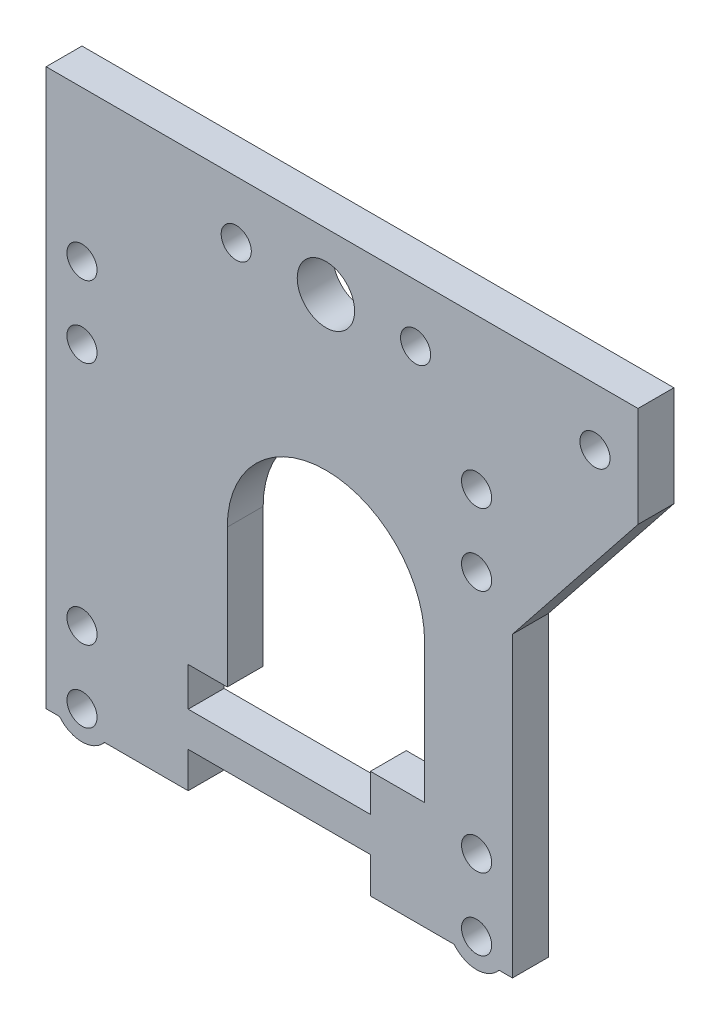
SolidWorks part; units mm, degrees
ref_plane "Front Plane" through (0, 0, 0) normal (0, 0, 1) x (1, 0, 0)
ref_plane "Top Plane" through (0, 0, 0) normal (0, 1, 0) x (1, 0, 0)
ref_plane "Right Plane" through (0, 0, 0) normal (1, 0, 0) x (0, 0, -1)
sketch "Sketch1" plane through (0, 0, 0) normal (0, 0, 1) x (1, 0, 0)
  line L1 (-65, 61.5) -> (0, 61.5)
  line L2 (-65, 61.5) -> (-65, 0)
  line L3 (-65, 0) -> (-63.1225, 0)
  line L4 (0, 61.5) -> (0, 0)
  line L5 (-56.8775, 0) -> (-45, 0)
  line L6 (-1.8775, 0) -> (0, 0)
  line L7 (-20, 0) -> (-8.1225, 0)
  line L9 (-45, 0) -> (-45, 5)
  line L10 (-45, 5) -> (-20, 5)
  line L11 (-20, 0) -> (-20, 5)
  line L13 (-45, 15.05) -> (-20, 15.05)
  line L14 (-45, 15.05) -> (-45, 9.95)
  line L15 (-45, 9.95) -> (-20, 9.95)
  line L16 (-20, 15.05) -> (-20, 9.95)
  circle A0 centre (-60, 56.5) radius 2.1
  circle A1 centre (-5, 56.5) radius 2.1
  circle A2 centre (-60, 46.5) radius 2.1
  circle A3 centre (-5, 46.5) radius 2.1
  circle A4 centre (-5, 12.5) radius 2.1
  circle A5 centre (-5, 2.5) radius 2.1
  circle A6 centre (-60, 2.5) radius 2.1
  circle A7 centre (-60, 12.5) radius 2.1
  arc A8 (-63.1225, 0) -> (-56.8775, 0) centre (-60, 2.5) ccw
  arc A9 (-8.1225, 0) -> (-1.8775, 0) centre (-5, 2.5) ccw
  point P35 (-45, 12.5)
  dimension "D1" = 4.2
  dimension "D2" = 4.2
  dimension "D3" = 4.2
  dimension "D4" = 4.2
  dimension "D5" = 5
  dimension "D6" = 5
  dimension "D7" = 10
  dimension "D8" = 10
  dimension "D9" = 5
  dimension "D11" = 55
  dimension "D14" = 8
  dimension "D15" = 8
  dimension "D10" = 5
  dimension "D12" = 61.5
  dimension "D16" = 5
  dimension "D17" = 20
  dimension "D18" = 20
  dimension "D19" = 25
  dimension "D20" = 15
  dimension "D21" = 5.1
extrude "Boss-Extrude1" add sketch "Sketch1" along normal blind 5
sketch "Sketch3" plane through (0, 0, 0) normal (0, 0, -1) x (-1, 0, 0)
  line L0 (39.75, 15.05) -> (39.75, 34.55)
  line L1 (20, 15.05) -> (45, 15.05) construction
  line L2 (12.25, 34.55) -> (12.25, 15.05)
  line L3 (39.75, 15.05) -> (12.25, 15.05)
  arc A0 (39.75, 34.55) -> (12.25, 34.55) centre (26, 34.55) ccw
  circle A1 centre (26, 34.55) radius 3.6 construction
  dimension "D1" = 27.5
extrude "Cut-Extrude2" cut sketch "Sketch3" against normal blind 5
sketch "Sketch4" plane through (0, 0, 0) normal (0, 0, -1) x (-1, 0, 0)
  line L0 (0, 41.5) -> (-17.5, 63.5)
  line L1 (-17.5, 63.5) -> (0, 41.5) construction
  line L2 (-17.5, 63.5) -> (-17.5, 77.5)
  line L5 (65, 61.5) -> (65, 77.5)
  line L10 (65, 77.5) -> (-17.5, 77.5)
  line L18 (65, 0) -> (65, 61.5)
  line L19 (65, 61.5) -> (0, 61.5)
  line L20 (0, 61.5) -> (0, 0)
  line L21 (0, 0) -> (1.8775, 0)
  line L22 (8.1225, 0) -> (20, 0)
  line L23 (20, 0) -> (20, 5)
  line L24 (20, 5) -> (45, 5)
  line L25 (45, 5) -> (45, 0)
  line L26 (45, 0) -> (56.8775, 0)
  line L27 (63.1225, 0) -> (65, 0)
  line L29 (65, 61.5) -> (0, 61.5)
  line L30 (0, 61.5) -> (0, 41.5)
  arc A0 (28.3171, 66.2394) -> (22.3115, 67.9523) centre (26, 69.5) ccw construction
  circle A1 centre (13.5, 69.5) radius 2.1 construction
  circle A2 centre (-11.5, 69.5) radius 2.1 construction
  circle A6 centre (38.5, 69.5) radius 2.1 construction
  circle A8 centre (-11.5, 69.5) radius 2.1
  arc A11 (1.8775, 0) -> (8.1225, 0) centre (5, 2.5) ccw
  arc A12 (56.8775, 0) -> (63.1225, 0) centre (60, 2.5) ccw
  circle A16 centre (13.5, 69.5) radius 2.1
  circle A17 centre (26, 69.5) radius 4
  circle A18 centre (38.5, 69.5) radius 2.1
  point P34 (13.5, 69.5)
  point P36 (-11.5, 69.5)
  point P37 (26, 69.5)
  point P39 (38.5, 69.5)
  dimension "D2" = 8
  dimension "D3" = 4.2
  dimension "D4" = 4.2
  dimension "D5" = 4.2
  dimension "D6" = 6
  dimension "D7" = 8
  dimension "D9" = 43.5
  dimension "D10" = 56
  dimension "D1" = 0
  dimension "D8" = 31
  dimension "D11" = 8
extrude "Boss-Extrude2" add sketch "Sketch4" against normal blind 5
sketch "Sketch5" plane through (0, 0, 0) normal (0, 0, -1) x (-1, 0, 0)
  line L0 (56.8775, 0) -> (45, 0) construction
  line L1 (19.8, 5) -> (45.2, 5)
  line L2 (19.8, 5) -> (19.8, 0)
  line L3 (19.8, 0) -> (45.2, 0)
  line L4 (45.2, 5) -> (45.2, 0)
  line L5 (20, 5) -> (20, 0) construction
  line L7 (12.25, 15.05) -> (20, 15.05) construction
  line L8 (45.2, 15.25) -> (19.8, 15.25)
  line L9 (45.2, 15.25) -> (45.2, 9.85)
  line L10 (45.2, 9.85) -> (19.8, 9.85)
  line L11 (19.8, 15.25) -> (19.8, 9.85)
  dimension "D1" = 25.4
  dimension "D2" = 0.2
  dimension "D3" = 5
  dimension "D4" = 5.4
  dimension "D5" = 0.2
  dimension "D6" = 25.4
extrude "Cut-Extrude3" cut sketch "Sketch5" against normal blind 10
